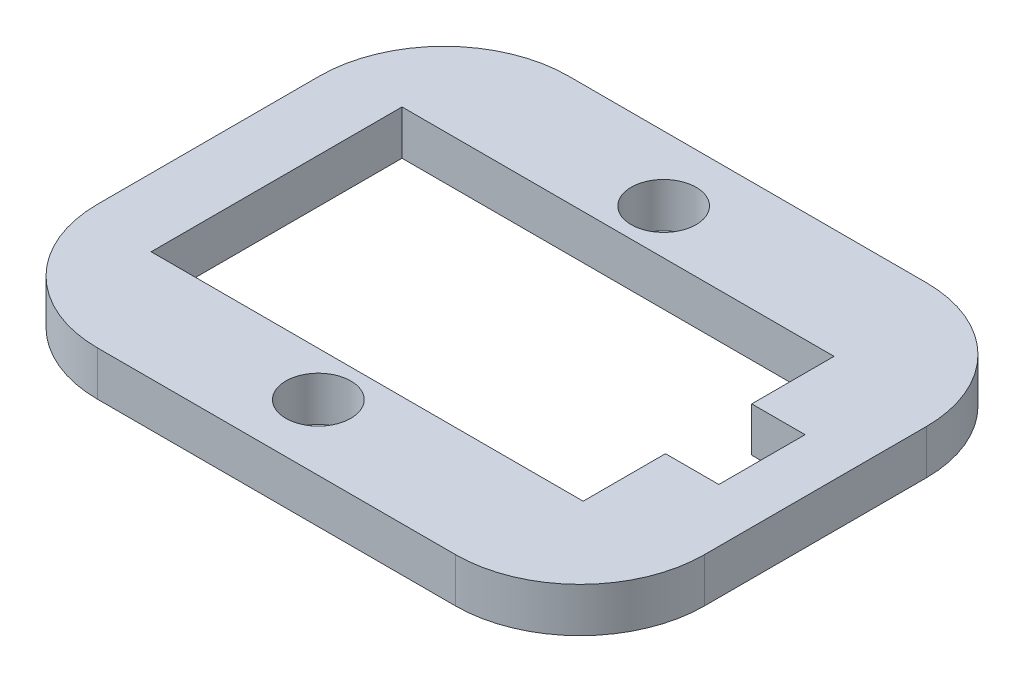
SolidWorks part; units mm, degrees
ref_plane "Front Plane" through (0, 0, 0) normal (0, 0, 1) x (1, 0, 0)
ref_plane "Top Plane" through (0, 0, 0) normal (0, 1, 0) x (1, 0, 0)
ref_plane "Right Plane" through (0, 0, 0) normal (1, 0, 0) x (0, 0, -1)
sketch "Sketch2" plane through (0, 0, 0) normal (0, 1, 0) x (1, 0, 0)
  line L0 (-12.8784, 7.8335) -> (11.4112, 7.8335)
  line L1 (-9.7015, 14.0166) -> (10.4229, 14.0166)
  line L2 (-16.7015, 7.0166) -> (-16.7015, -5.4616)
  line L3 (-9.7015, -12.4616) -> (10.4229, -12.4616)
  line L4 (17.4229, 7.0166) -> (17.4229, -5.4616)
  line L5 (11.4112, 7.8335) -> (11.4112, 3.2059)
  line L6 (11.4112, 3.2059) -> (14.4112, 3.2059)
  line L7 (14.4112, 3.2059) -> (14.4112, -1.6439)
  line L8 (14.4112, -1.6439) -> (11.4112, -1.6439)
  line L9 (11.4112, -1.6439) -> (11.4112, -6.2716)
  line L10 (11.4112, -6.2716) -> (-12.8784, -6.2716)
  line L11 (-12.8784, -6.2716) -> (-12.8784, 7.8335)
  circle A0 centre (-0.7026, 10.3665) radius 1.825
  circle A1 centre (-0.978, -8.7735) radius 1.825
  arc A2 (-16.7015, -5.4616) -> (-9.7015, -12.4616) centre (-9.7015, -5.4616) ccw
  arc A3 (10.4229, -12.4616) -> (17.4229, -5.4616) centre (10.4229, -5.4616) ccw
  arc A4 (10.4229, 14.0166) -> (17.4229, 7.0166) centre (10.4229, 7.0166) cw
  arc A5 (-9.7015, 14.0166) -> (-16.7015, 7.0166) centre (-9.7015, 7.0166) ccw
  dimension "D8" = 3.65
  dimension "D1" = 19.14
  dimension "D2" = 7
  dimension "D3" = 4.6277
  dimension "D4" = 24.2896
  dimension "D5" = 3
  dimension "D6" = 4.8498
extrude "Boss-Extrude1" add sketch "Sketch2" along normal mid plane 2.5
